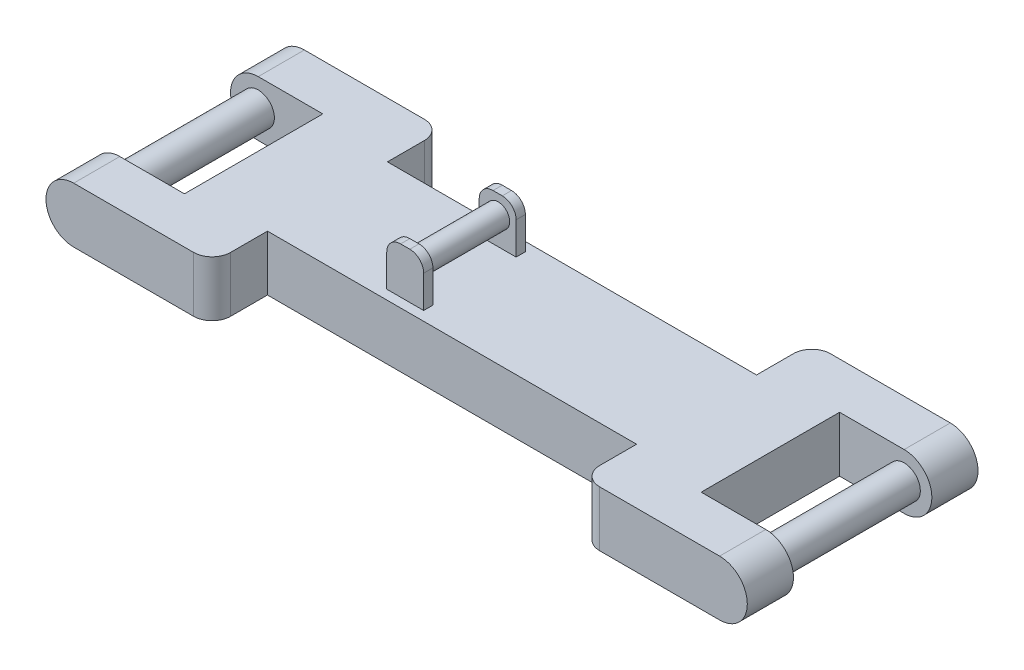
SolidWorks part; units mm, degrees
ref_plane "Front Plane" through (0, 0, 0) normal (0, 0, 1) x (1, 0, 0)
ref_plane "Top Plane" through (0, 0, 0) normal (0, 1, 0) x (1, 0, 0)
ref_plane "Right Plane" through (0, 0, 0) normal (1, 0, 0) x (0, 0, -1)
sketch "Sketch1" plane through (0, 0, 0) normal (0, 0, 1) x (1, 0, 0)
  line L0 (-175, 0) -> (175, 0) construction
  line L1 (-175, 15) -> (175, 15)
  line L2 (-175, -15) -> (175, -15)
  arc A0 (-175, 15) -> (-175, -15) centre (-175, 0) ccw
  arc A1 (175, -15) -> (175, 15) centre (175, 0) ccw
  point P2 (0, 0)
  dimension "D2" = 15
  dimension "D1" = 350
extrude "Boss-Extrude1" add sketch "Sketch1" along normal blind 125
sketch "Sketch2" plane through (0, 15, 0) normal (0, 1, 0) x (1, 0, 0)
  line L1 (-140, -25) -> (-190, -25)
  line L2 (-140, -25) -> (-140, -100)
  line L3 (-140, -100) -> (-190, -100)
  line L4 (-190, -25) -> (-190, -100)
  line L5 (-190, 0) -> (-190, -125) construction
  line L6 (175, -125) -> (175, 0) construction
  line L7 (0, 0) -> (0, -42.2744)
  line L8 (175, 0) -> (-175, 0) construction
  line L9 (190, -25) -> (190, -100)
  line L10 (140, -100) -> (190, -100)
  line L11 (140, -25) -> (140, -100)
  line L12 (140, -25) -> (190, -25)
  point P10 (175, -62.5)
  point P11 (-140, -62.5)
  line M3 (-175, 0) -> (-175, -125)
  line M5 (175, -125) -> (175, 0)
  dimension "D1" = 75
  dimension "D2" = 50
extrude "Cut-Extrude1" cut sketch "Sketch2" against normal blind 100 contours L3 L2 L1 M3 | L1 L4 L3 M3 | L12 L10 L9 M5 | L12 L11 L10 M5
sketch "Sketch3" plane through (0, 0, 25) normal (0, 0, 1) x (1, 0, 0)
  line L0 (0, 15) -> (0, 0)
  line L1 (175, 15) -> (-175, 15) construction
  circle A0 centre (-175, 0) radius 8.75
  circle A1 centre (175, 0) radius 8.75
  dimension "D1" = 17.5
extrude "Boss-Extrude2" add sketch "Sketch3" along normal up to surface (75 mm away) contours A0 | A1 up to face at (-161.25, 0, 100)
sketch "Sketch4" plane through (0, 15, 0) normal (0, 1, 0) x (1, 0, 0)
  line L0 (175, -125) -> (-175, -125) construction
  line L1 (-100, -125) -> (100, -125)
  line L2 (-100, -125) -> (-100, -95)
  line L3 (-100, -95) -> (100, -95)
  line L4 (100, -125) -> (100, -95)
  line L5 (140, -62.5) -> (104.7907, -62.5)
  line L6 (140, -25) -> (140, -100) construction
  line L7 (100, 0) -> (100, -30)
  line L8 (-100, -30) -> (100, -30)
  line L9 (-100, 0) -> (-100, -30)
  line L10 (-100, 0) -> (100, 0)
  point P14 (0, -125)
  line M12 (-175, -125) -> (175, -125)
  line M18 (175, 0) -> (-175, 0)
  dimension "D1" = 200
  dimension "D2" = 30
extrude "Cut-Extrude2" cut sketch "Sketch4" against normal through all contours L9 L8 L7 M18 | L4 L3 L2 M12
fillet "Fillet1" radius 10 4 edges at (100, 0, 125) (100, 0, 0) (-100, 0, 0) (-100, 0, 125)
ref_plane "Plane1" through (0, 0, 62.5) normal (0, 0, 1) x (1, 0, 0)
sketch "Sketch6" plane through (0, 0, 62.5) normal (0, 0, 1) x (1, 0, 0)
  circle A0 centre (-30, 30) radius 6.25
  dimension "D1" = 12.5
  dimension "D2" = 30
  dimension "D3" = 30
extrude "Boss-Extrude3" add sketch "Sketch6" along normal mid plane 45 separate body
sketch "Sketch7" plane through (0, 0, 0) normal (0, 1, 0) x (1, 0, 0)
  line L5 (-20.4333, -84.9338) -> (-40.4333, -84.9338)
  line L7 (-20.4333, -84.9338) -> (-20.4333, -89.9338)
  line L8 (-20.4333, -89.9338) -> (-40.4333, -89.9338)
  line L12 (-40.4333, -84.9338) -> (-40.4333, -89.9338)
  line L13 (-40.4333, -39.8334) -> (-20.4333, -39.8334)
  line L14 (-40.4333, -39.8334) -> (-40.4333, -34.8334)
  line L15 (-40.4333, -34.8334) -> (-20.4333, -34.8334)
  line L16 (-20.4333, -39.8334) -> (-20.4333, -34.8334)
  dimension "D1" = 5
  dimension "D2" = 20
  dimension "D3" = 5
extrude "Boss-Extrude4" add sketch "Sketch7" along normal blind 40
fillet "Fillet2" radius 7.5 4 edges at (-40.4333, 40, 37.3334) (-20.4333, 40, 37.3334) (-40.4333, 40, 87.4338) (-20.4333, 40, 87.4338)
